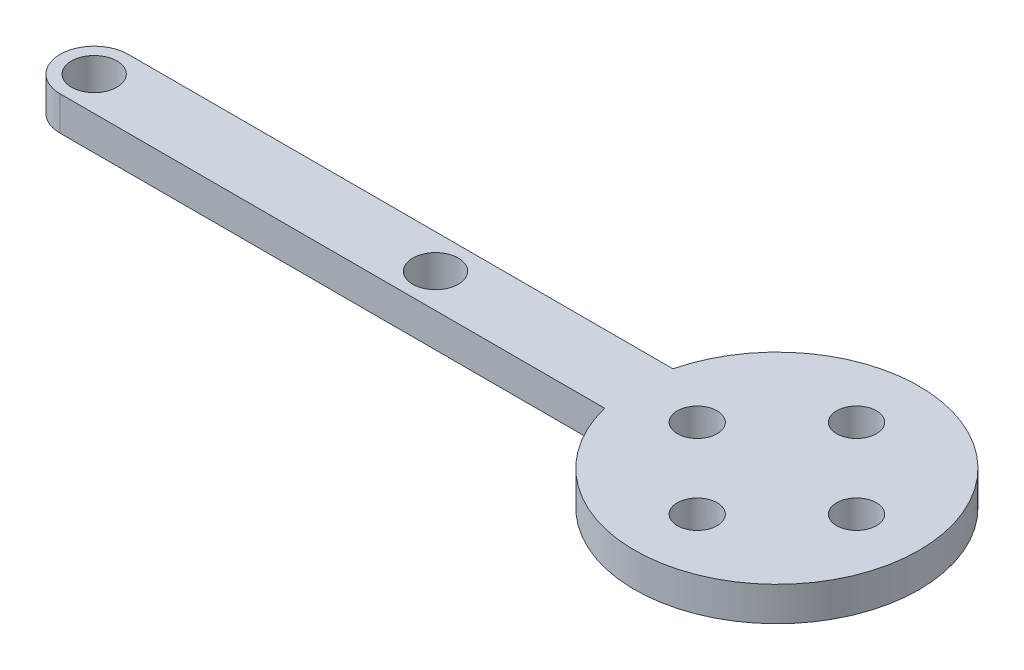
SolidWorks part; units mm, degrees
ref_plane "前视基准面" through (0, 0, 0) normal (0, 0, 1) x (1, 0, 0)
ref_plane "上视基准面" through (0, 0, 0) normal (0, 1, 0) x (1, 0, 0)
ref_plane "右视基准面" through (0, 0, 0) normal (1, 0, 0) x (0, 0, -1)
sketch "草图1" plane through (0, 0, 0) normal (0, 1, 0) x (1, 0, 0)
  line L0 (0, 0) -> (0, 7) construction
  line L1 (0, 0) -> (-60, 0) construction
  line L2 (-12.1347, -3) -> (-60, -3)
  line L3 (-12.1347, 3) -> (-60, 3)
  arc A0 (-12.1347, -3) -> (-12.1347, 3) centre (0, 0) ccw
  circle A1 centre (0, 7) radius 1.75
  circle A2 centre (7, 0) radius 1.75
  circle A3 centre (0, -7) radius 1.75
  circle A4 centre (-7, 0) radius 1.75
  arc A6 (-60, 3) -> (-60, -3) centre (-60, 0) ccw
  circle A7 centre (-60, 0) radius 2
  circle A8 centre (-30, 0) radius 2
  point P5 (-30, 0)
  point P14 (0, 0)
  point P20 (-12.1347, 3)
  point P21 (-12.1347, -3)
  dimension "D1" = 3.5
  dimension "D4" = 25
  dimension "D7" = 4
  dimension "D8" = 4
  dimension "D3" = 14
  dimension "D5" = 6
  dimension "D6" = 60
  dimension "D2" = 4
extrude "凸台-拉伸1" add sketch "草图1" along normal blind 3
